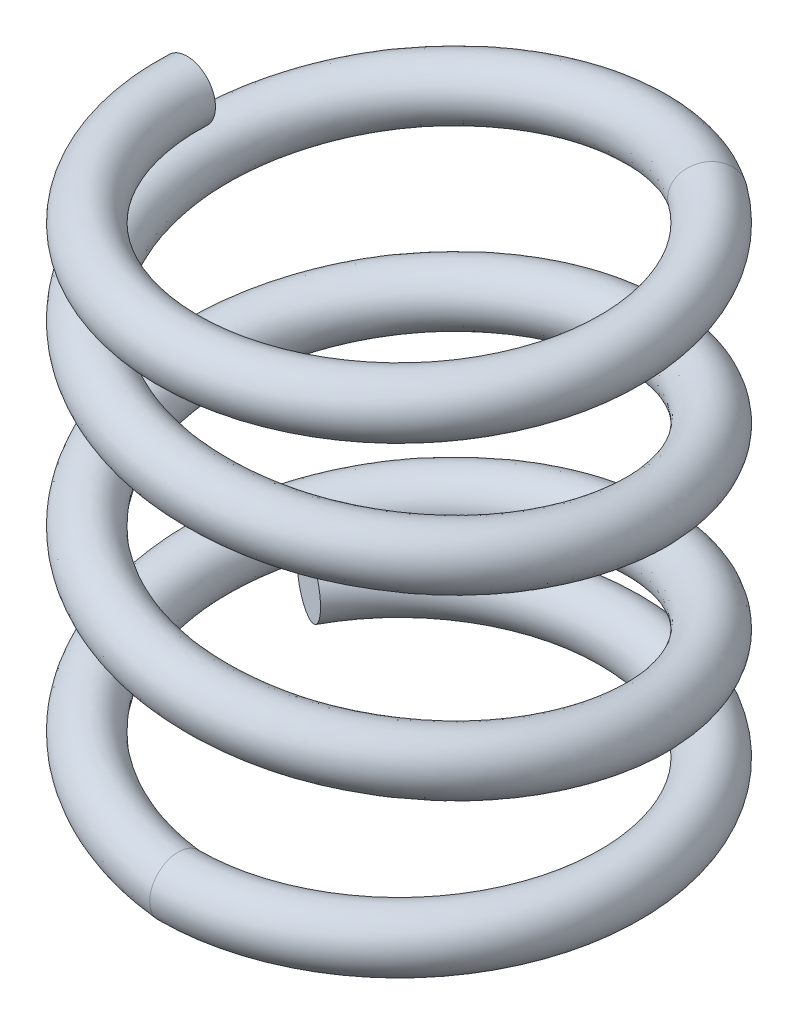
SolidWorks part; units mm, degrees
ref_plane "Front Plane" through (0, 0, 0) normal (0, 0, 1) x (1, 0, 0)
ref_plane "Top Plane" through (0, 0, 0) normal (0, 1, 0) x (1, 0, 0)
ref_plane "Right Plane" through (0, 0, 0) normal (1, 0, 0) x (0, 0, -1)
sketch "Sketch1" plane through (0, 0, 0) normal (0, 1, 0) x (1, 0, 0)
  circle A0 centre (0, 0) radius 3.1
  dimension "D1" = 6.2
curve "Helix/Spiral1" pitch 2.5 height 6.5 turns 2.6
sketch "Sketch3" plane through (0, 0, 0) normal (1, 0, 0) x (0, 0, -1)
  circle A0 centre (-3.1, 0) radius 0.4
  spline S0 degree 3 poles (-3.1, 0) (-3.1, 0.0525) (-2.9338, 0.1587) (-2.2248, 0.317) (-1.1672, 0.4756) (0.0732, 0.6341) (1.3021, 0.7927) (2.3271, 0.9512) (2.9874, 1.1098) (3.1798, 1.2683) (2.8739, 1.4268) (2.1178, 1.5854) (1.0299, 1.7439) (-0.2193, 1.9024) (-1.4342, 2.061) (-2.4244, 2.2195) (-3.0348, 2.378) (-3.1697, 2.5366) (-2.808, 2.6951) (-2.0064, 2.8537) (-0.8904, 3.0122) (0.3651, 3.1707) (1.5633, 3.3293) (2.5166, 3.4878) (3.0757, 3.6463) (3.1529, 3.8049) (2.7361, 3.9634) (1.8907, 4.122) (0.749, 4.2805) (-0.51, 4.439) (-1.6891, 4.5976) (-2.6036, 4.7561) (-3.1101, 4.9146) (-3.1294, 5.0732) (-2.6585, 5.2317) (-1.771, 5.3902) (-0.606, 5.5488) (0.6539, 5.7073) (1.8113, 5.8659) (2.685, 6.0244) (3.1378, 6.183) (3.1001, 6.3413) (2.7484, 6.4475) (2.508, 6.5) knots 0 0 0 0 0.02439 0.04878 0.073171 0.097561 0.121951 0.146341 0.170732 0.195122 0.219512 0.243902 0.268293 0.292683 0.317073 0.341463 0.365854 0.390244 0.414634 0.439024 0.463415 0.487805 0.512195 0.536585 0.560976 0.585366 0.609756 0.634146 0.658537 0.682927 0.707317 0.731707 0.756098 0.780488 0.804878 0.829268 0.853659 0.878049 0.902439 0.926829 0.95122 0.97561 1 1 1 1 construction
  dimension "D1" = 0.8
sweep "Sweep2" add profiles "Sketch3" path "Helix/Spiral1"
sketch "Sketch7" plane through (0, 0, 0) normal (0, 1, 0) x (1, 0, 0)
  line L0 (0, -3.5) -> (0, -2.7) construction
  arc A0 (0, -3.1) -> (-2.7314, 1.4662) centre (0, 0) ccw
  dimension "D1" = 6.2
sketch "Sketch8" plane through (0, 0, 0) normal (1, 0, 0) x (0, 0, -1)
  line L0 (3.1, 0) -> (-3.1, 0) construction
  circle A0 centre (-3.1, 0) radius 0.4
sweep "Sweep3" add profiles "Sketch8" path "Sketch7"
sketch "Sketch10" plane through (0, 0, 0) normal (0.809, 0, 0.5878) x (0.5878, 0, -0.809)
  circle A0 centre (3.1, 6.5) radius 0.4
  circle A1 centre (3.1, 6.5) radius 0.4 construction
  point P2 (3.1, 6.5)
ref_plane "Plane1" through (0, 6.5, 0) normal (0, 1, 0) x (1, 0, 0)
sketch "Sketch12" plane through (0, 6.5, 0) normal (0, 1, 0) x (1, 0, 0)
  arc A0 (1.8221, 2.508) -> (-3.0969, 0.1388) centre (0, 0) cw
sweep "Sweep4" add profiles "Sketch10" path "Sketch12"
sketch "Sketch4" plane through (0, 0, 0) normal (1, 0, 0) x (0, 0, -1)
  line L0 (0.3739, 6.9) -> (0.1389, 6.9) construction
  line L1 (-3.1, -0.4) -> (-4.5425, -0.4) construction
  circle A3 centre (-3.1, 0) radius 0.4 construction
  ellipse E0 centre (0.1388, 6.5) end of major axis (0.1388, 6.1) minor radius 0.0179 construction
sketch "Sketch5" plane through (0, 0, 0) normal (0, 1, 0) x (1, 0, 0)
  circle A0 centre (0, 0) radius 3.5 construction
  circle A1 centre (0, 0) radius 2.7 construction
  circle A2 centre (0, 0) radius 3.1 construction
  dimension "D1" = 7
  dimension "D2" = 6.2
  dimension "D3" = 5.4
